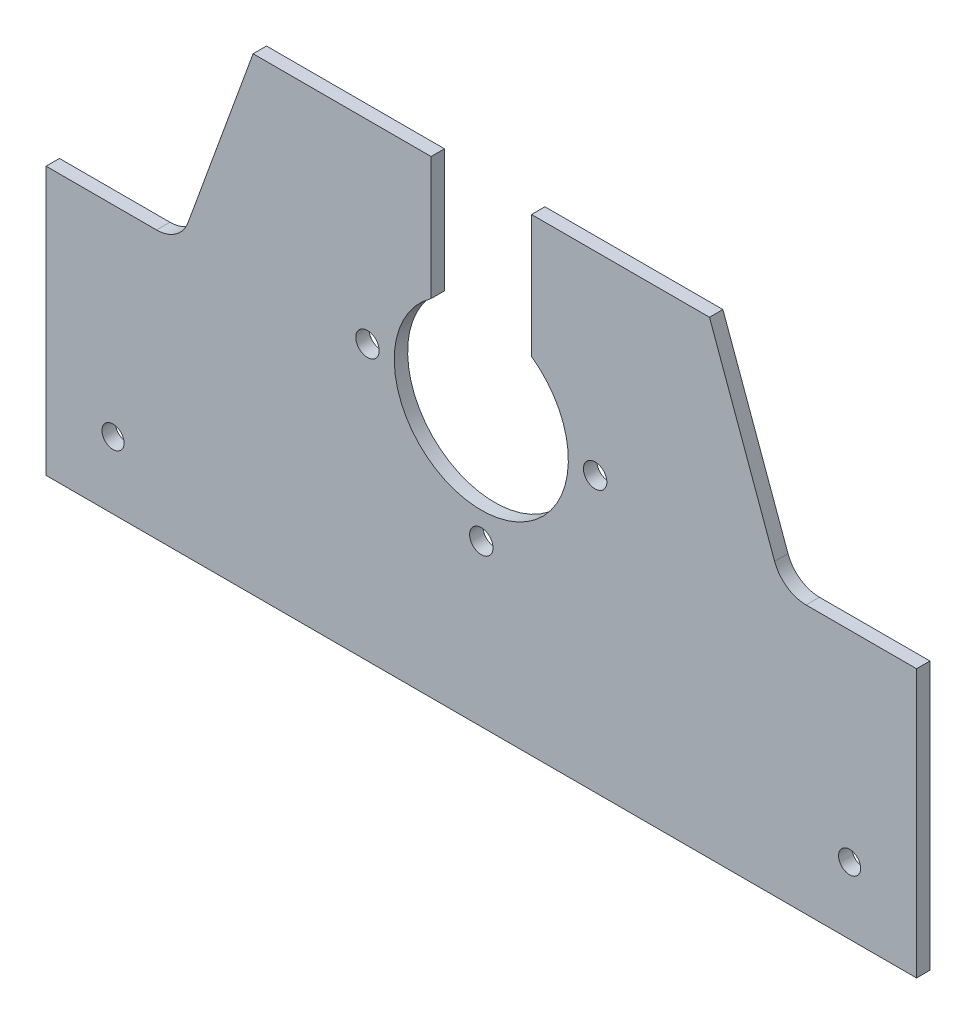
SolidWorks part; units mm, degrees
ref_plane "前视基准面" through (0, 0, 0) normal (0, 0, 1) x (1, 0, 0)
ref_plane "上视基准面" through (0, 0, 0) normal (0, 1, 0) x (1, 0, 0)
ref_plane "右视基准面" through (0, 0, 0) normal (1, 0, 0) x (0, 0, -1)
other "Configuration Table"
sketch "草图1" plane through (0, 0, 0) normal (0, 0, 1) x (1, 0, 0)
  line L0 (-43.8026, 23.2899) -> (-34.0809, 50)
  line L1 (-65, -20) -> (65, -20)
  line L2 (-65, -20) -> (-65, 20)
  line L3 (-65, 20) -> (-48.501, 20)
  line L4 (65, -20) -> (65, 20)
  line L5 (-65, -20) -> (65, 20) construction
  line L6 (-65, 20) -> (65, -20) construction
  line L7 (-34.0809, 50) -> (34.0809, 50)
  line L8 (0, 50) -> (0, 0) construction
  line L9 (43.8026, 23.2899) -> (34.0809, 50)
  line L10 (48.501, 20) -> (65, 20)
  arc A0 (43.8026, 23.2899) -> (48.501, 20) centre (48.501, 25) ccw
  arc A1 (-43.8026, 23.2899) -> (-48.501, 20) centre (-48.501, 25) cw
  point P0 (0, 0)
  point P14 (45, 20)
  point P17 (-45, 20)
  dimension "D6" = 5
  dimension "D1" = 130
  dimension "D2" = 40
  dimension "D3" = 20
  dimension "D4" = 30
  dimension "D5" = 70
extrude "凸台-拉伸1" add sketch "草图1" along normal blind 2
sketch "草图2" plane through (0, 0, 0) normal (0, 0, 1) x (1, 0, 0)
  line L0 (-65, -10) -> (65, -10) construction
  line L1 (-65, 20) -> (-65, -20) construction
  line L2 (65, -20) -> (65, 20) construction
  line L3 (-65, -20) -> (65, -20) construction
  line L4 (0, 0) -> (0, -20) construction
  circle A0 centre (-55, -10) radius 1.65
  circle A1 centre (55, -10) radius 1.65
  dimension "D2" = 3.3
  dimension "D1" = 10
  dimension "D3" = 10
extrude "切除-拉伸1" cut sketch "草图2" along normal blind 2
sketch "草图3" plane through (0, 0, 0) normal (0, 0, 1) x (1, 0, 0)
  line L0 (0, 50) -> (0, -20) construction
  line L1 (34.0809, 50) -> (-34.0809, 50) construction
  line L2 (-65, -20) -> (65, -20) construction
  line L3 (12.5, 42.6506) -> (0, 21) construction
  line L4 (21.6506, 33.5) -> (0, 21) construction
  line L5 (21.6506, 8.5) -> (0, 21) construction
  circle A0 centre (0, 21) radius 17 construction
  circle A1 centre (0, 38) radius 1.75
  circle A2 centre (17, 21) radius 1.75
  circle A3 centre (0, 4) radius 1.75
  circle A4 centre (-17, 21) radius 1.75
  circle A5 centre (0, 21) radius 13
  point P18 (0, 21)
  dimension "D2" = 34
  dimension "D3" = 3.5
  dimension "D5" = 26
  dimension "D1" = 41
  dimension "D8" = 30
  dimension "D9" = 30
  dimension "D10" = 60
  dimension "D4" = 4
extrude "切除-拉伸2" cut sketch "草图3" along normal blind 2
sketch "草图4" plane through (0, 0, 2) normal (0, 0, 1) x (1, 0, 0)
  line L0 (-7.5, 50) -> (-7.5, 27.252)
  line L1 (34.0809, 50) -> (-34.0809, 50) construction
  line L2 (-7.5, 27.252) -> (7.5, 27.252)
  line L3 (7.5, 27.252) -> (7.5, 50)
  line L4 (-7.5, 50) -> (7.5, 50)
  line L5 (0, 0) -> (0, 50) construction
  point P9 (3.1618, 50)
  dimension "D1" = 15
extrude "切除-拉伸3" cut sketch "草图4" against normal mid plane 10
